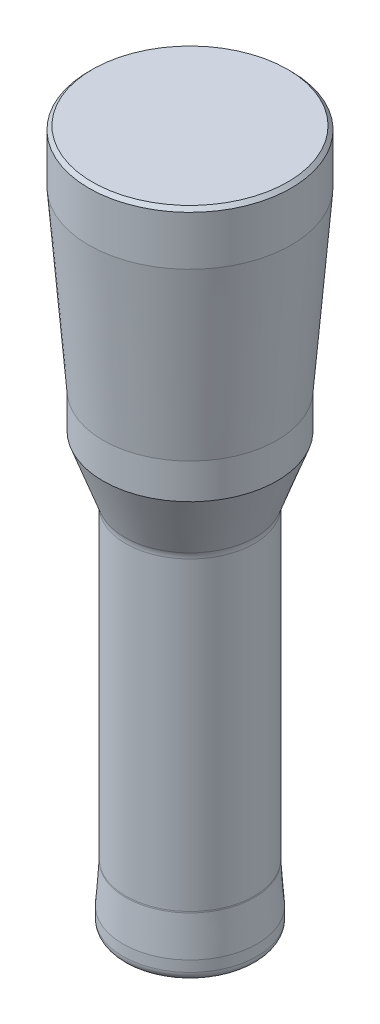
SolidWorks part; units mm, degrees
ref_plane "Płaszczyzna przednia" through (0, 0, 0) normal (0, 0, 1) x (1, 0, 0)
ref_plane "Płaszczyzna górna" through (0, 0, 0) normal (0, 1, 0) x (1, 0, 0)
ref_plane "Płaszczyzna prawa" through (0, 0, 0) normal (1, 0, 0) x (0, 0, -1)
sketch "Szkic1" plane through (0, 0, 0) normal (0, 0, 1) x (1, 0, 0)
  line L0 (0, 246.2452) -> (0, -53.5473) construction
  line L1 (0, 0) -> (-11.5412, 0)
  line L2 (-11.5412, 0) -> (-16.7169, 0.6814)
  line L3 (0, 198.039) -> (0, 0)
  line L4 (-11.5412, 0) -> (-1.6159, -1.3067) construction
  line L6 (-19.02, 6.3644) -> (-19.02, 0.9714) construction
  line L7 (-19.02, 6.3644) -> (-19.02, 3.3075)
  line L8 (-19.02, 3.3075) -> (-19.02, 6.3644)
  line L9 (-18.2489, 17.391) -> (-19.02, 6.3644)
  line L10 (-18.2368, 104.3998) -> (-18.2368, 17.7398)
  line L11 (-18.2368, 17.5652) -> (-18.2368, 3.8622) construction
  line L13 (-18.5383, 106.1099) -> (-24.7, 123.039)
  line L14 (-18.2368, 105.2814) -> (-18.2368, 125.9584) construction
  line L17 (-24.7, 123.039) -> (-24.7, 133.039)
  line L18 (-28.72, 183.039) -> (-28.72, 198.039)
  line L19 (-28.72, 183.039) -> (-24.7, 133.039) construction
  line L20 (-28.72, 183.039) -> (-28.72, 181.6063) construction
  line L21 (-24.7, 133.039) -> (-28.72, 183.039)
  line L24 (-28.72, 198.039) -> (0, 198.039)
  arc A0 (-19.02, 3.3075) -> (-16.7169, 0.6814) centre (-16.3712, 3.3075) ccw
  arc A1 (-18.2368, 104.3998) -> (-18.5383, 106.1099) centre (-23.2368, 104.3998) ccw
  arc A2 (-18.2368, 17.7398) -> (-18.2489, 17.391) centre (-23.2368, 17.7398) cw
  dimension "D2" = 2.6488
  dimension "D13" = 5
  dimension "D14" = 5
  dimension "D3" = 86.66
  dimension "D4" = 4
  dimension "D5" = 15
  dimension "D6" = 11.5412
  dimension "D7" = 20
  dimension "D8" = 28.72
  dimension "D9" = 10
  dimension "D10" = 50
  dimension "D11" = 3.0568
  dimension "D12" = 4.597
  dimension "D15" = 19.02
  dimension "D16" = 7.5
revolve "Obrót5" add sketch "Szkic1" angle 360 about L3
chamfer "Sfazowanie1" distance 1 angle 45 1 edges at (0, 198.039, 28.72)
